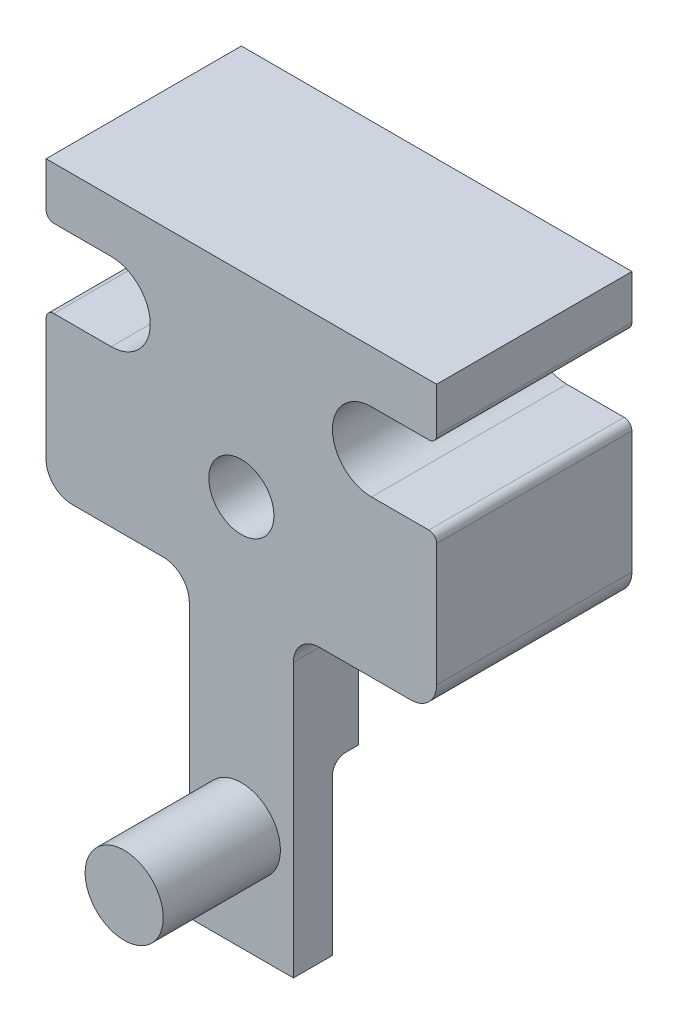
SolidWorks part; units mm, degrees
ref_plane "前视基准面" through (0, 0, 0) normal (0, 0, 1) x (1, 0, 0)
ref_plane "上视基准面" through (0, 0, 0) normal (0, 1, 0) x (1, 0, 0)
ref_plane "右视基准面" through (0, 0, 0) normal (1, 0, 0) x (0, 0, -1)
sketch "草图1" plane through (0, 0, 0) normal (0, 0, 1) x (1, 0, 0)
  line L0 (0, 10.5509) -> (0, -10.9916) construction
  line L1 (-7.5, -5.5) -> (7.5, -5.5)
  line L2 (-7.5, -5.5) -> (-7.5, 5.5)
  line L3 (-7.5, 5.5) -> (7.5, 5.5)
  line L4 (7.5, -5.5) -> (7.5, 5.5)
  line L5 (-7.5, -5.5) -> (7.5, 5.5) construction
  line L6 (-7.5, 5.5) -> (7.5, -5.5) construction
  line L7 (-7.5, 3.5) -> (-5, 3.5)
  line L8 (-5, 3.5) -> (-5, 0.5) construction
  line L9 (-5, 0.5) -> (-7.5, 0.5)
  line L10 (5, 3.5) -> (5, 0.5) construction
  line L11 (5, 0.5) -> (7.5, 0.5)
  line L12 (7.5, 3.5) -> (5, 3.5)
  arc A0 (-5, 0.5) -> (-5, 3.5) centre (-5, 2) ccw
  arc A1 (5, 0.5) -> (5, 3.5) centre (5, 2) cw
  point P0 (0, 0)
  dimension "D1" = 15
  dimension "D2" = 11
  dimension "D3" = 2
  dimension "D4" = 3
  dimension "D5" = 2.5
extrude "凸台-拉伸1" add sketch "草图1" along normal blind 7.5 contours L11 A1 L12 L4 L3 L2 L7 A0 L9 L1
fillet "圆角1" radius 0.3 4 edges at (7.5, 0.5, 3.75) (7.5, 3.5, 3.75) (-7.5, 0.5, 3.75) (-7.5, 3.5, 3.75)
fillet "圆角2" radius 1 2 edges at (7.5, -5.5, 3.75) (-7.5, -5.5, 3.75)
sketch "草图2" plane through (0, 0, 7.5) normal (0, 0, 1) x (1, 0, 0)
  circle A0 centre (0, -2) radius 1.5
  circle A1 centre (-5, 2) radius 1.5
  dimension "D1" = 3
  dimension "D4" = 3
  dimension "D2" = 4
  dimension "D3" = 5
hole_wizard "M3 螺纹孔1" positions "3D草图2" profile "草图3" tap size "M3" standard "GB" end condition through all
sketch3d "3D草图2"
  point P0 (0, -2, 7.5)
cosmetic thread "孔螺蚊线1" parameters "D2"=3
sketch "草图3" plane through (0, -2, 7.5) normal (1, 0, 0) x (0, -1, 0)
  line L0 (0, 0) -> (0, 7.5)
  line L1 (0, 7.5) -> (1.25, 7.5)
  line L2 (1.25, 7.5) -> (1.25, 0)
  line L5 (1.25, 0) -> (0, 0)
  line L11 (0, -6.35) -> (0, 107.95) construction
  dimension "通孔螺纹孔钻头直径" = 2.5
  dimension "通孔螺纹孔钻头深度" = 7.5
sketch "草图4" plane through (0, 0, 7.5) normal (0, 0, 1) x (1, 0, 0)
  line L0 (0, 12.2178) -> (0, -12.0464) construction
  line L1 (-2, -5.5) -> (-2, -10.5)
  line L2 (-6.5, -5.5) -> (6.5, -5.5) construction
  line L3 (-2, -10.5) -> (2, -10.5)
  line L4 (-2, -5.5) -> (2, -5.5)
  line L5 (2, -5.5) -> (2, -10.5)
  point P10 (0, -5.5)
  point P11 (0, -10.5)
  dimension "D1" = 5
  dimension "D2" = 2
extrude "凸台-拉伸2" add sketch "草图4" against normal blind 2.5
sketch "草图5" plane through (0, 0, 7.5) normal (0, 0, 1) x (1, 0, 0)
  line L0 (0, 7.5651) -> (0, -17.9363) construction
  line L1 (2, -10.5) -> (-2, -10.5)
  line L2 (-2, -10.5) -> (2, -10.5) construction
  line L3 (-2, -10.5) -> (-2, -17)
  line L4 (-2, -17) -> (2, -17)
  line L5 (2, -10.5) -> (2, -17)
  point P8 (0, -17.9363)
  point P12 (0, -10.5)
  point P13 (0, -17)
  dimension "D1" = 6.5
extrude "凸台-拉伸3" add sketch "草图5" against normal blind 1.5
fillet "圆角3" radius 0.5 1 edges at (0, -10.5, 6)
ref_plane "基准面1" through (0, 0, 0) normal (-1, 0, 0) x (0, 0, 1)
sketch "草图6" plane through (0, 0, 0) normal (-1, 0, 0) x (0, 0, 1)
  line L0 (5, -7) -> (3.5, -5.5)
  line L1 (5, -5.5) -> (5, -10.5) construction
  line L2 (7.5, -5.5) -> (0, -5.5) construction
  line L3 (3.5, -5.5) -> (5, -5.5)
  line L4 (5, -5.5) -> (5, -7)
  dimension "D1" = 1.5
  dimension "D2" = 1.5
extrude "凸台-拉伸4" add sketch "草图6" along normal blind 1 and the other way blind 1
fillet "圆角4" radius 1 4 edges at (2, -5.5, 6.25) (-2, -5.5, 6.25) (0, -5.5, 3.5) (0, -7, 5)
sketch "草图7" plane through (0, 0, 7.5) normal (0, 0, 1) x (1, 0, 0)
  line L0 (0, 6.7856) -> (0, -19.9302) construction
  line L1 (-2, -17) -> (2, -17) construction
  circle A0 centre (0, -13) radius 1.5
  dimension "D1" = 3
  dimension "D2" = 4
extrude "凸台-拉伸5" add sketch "草图7" along normal blind 4.5
